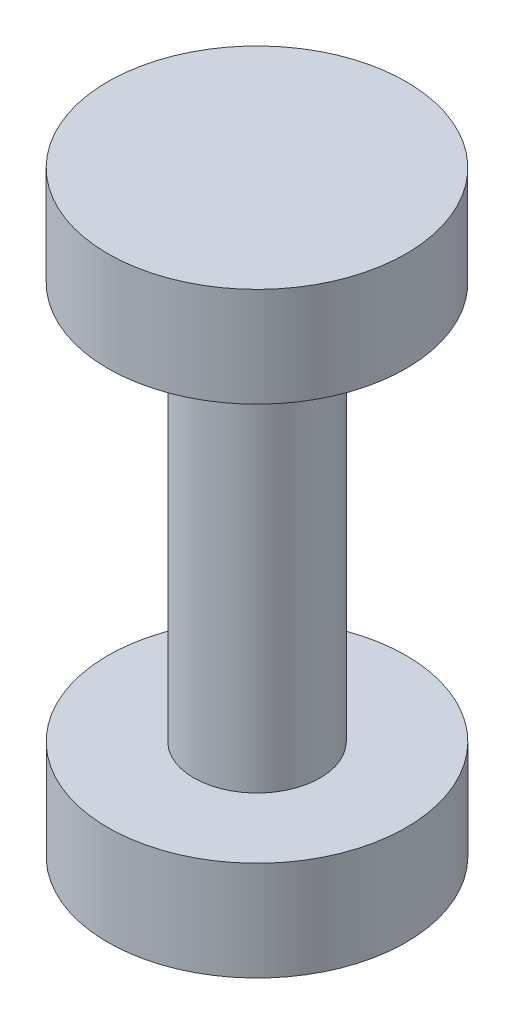
SolidWorks part; units mm, degrees
ref_plane "Front Plane" through (0, 0, 0) normal (0, 0, 1) x (1, 0, 0)
ref_plane "Top Plane" through (0, 0, 0) normal (0, 1, 0) x (1, 0, 0)
ref_plane "Right Plane" through (0, 0, 0) normal (1, 0, 0) x (0, 0, -1)
sketch "Sketch1" plane through (0, 0, 0) normal (0, 1, 0) x (1, 0, 0)
  circle A0 centre (0, 0) radius 3.175
  dimension "D1" = 6.35
extrude "Boss-Extrude1" add sketch "Sketch1" along normal blind 20
sketch "Sketch2" plane through (0, 20, 0) normal (0, 1, 0) x (1, 0, 0)
  circle A0 centre (0, 0) radius 7.5
  dimension "D1" = 15
extrude "Boss-Extrude2" add sketch "Sketch2" along normal blind 5
sketch "Sketch3" plane through (0, 0, 0) normal (0, -1, 0) x (1, 0, 0)
  circle A0 centre (0, 0) radius 7.5
  dimension "D1" = 15
extrude "Boss-Extrude3" add sketch "Sketch3" along normal blind 5
